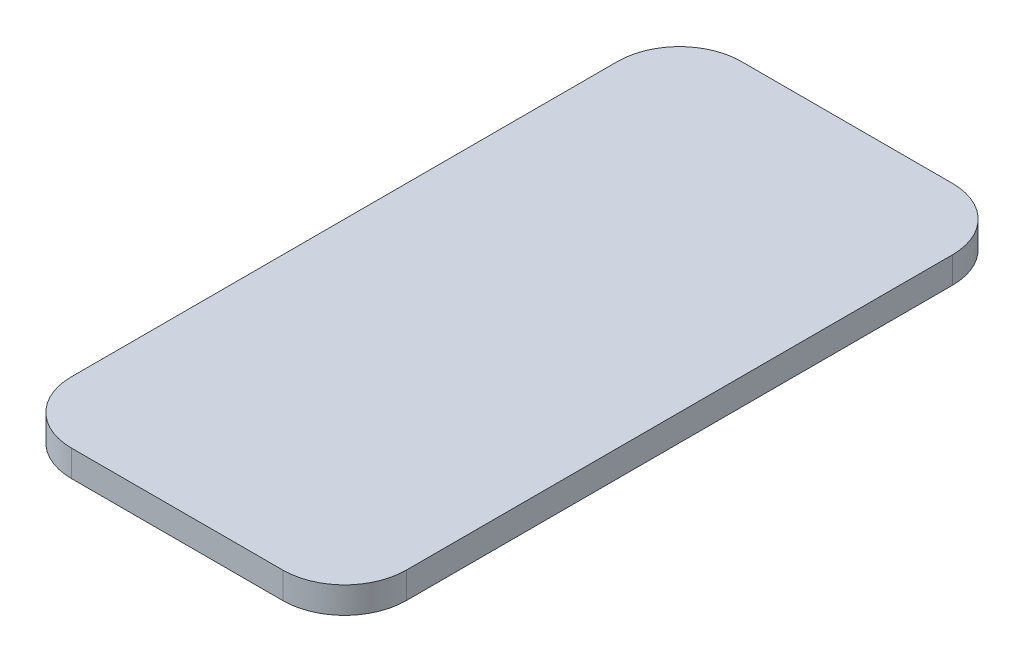
SolidWorks part; units mm, degrees
material "EN8"
ref_plane "Front Plane" through (0, 0, 0) normal (0, 0, 1) x (1, 0, 0)
ref_plane "Top Plane" through (0, 0, 0) normal (0, 1, 0) x (1, 0, 0)
ref_plane "Right Plane" through (0, 0, 0) normal (1, 0, 0) x (0, 0, -1)
sketch "Sketch1" plane through (0, 0, 0) normal (0, 1, 0) x (1, 0, 0)
  line L1 (-12, -38) -> (12, -38)
  line L2 (-19, -31) -> (-19, 31)
  line L3 (-12, 38) -> (12, 38)
  line L4 (19, -31) -> (19, 31)
  line L5 (-19, -38) -> (19, 38) construction
  line L6 (-19, 38) -> (19, -38) construction
  arc A0 (-12, -38) -> (-19, -31) centre (-12, -31) cw
  arc A1 (12, -38) -> (19, -31) centre (12, -31) ccw
  arc A2 (12, 38) -> (19, 31) centre (12, 31) cw
  arc A3 (-19, 31) -> (-12, 38) centre (-12, 31) cw
  point P0 (0, 0)
  dimension "D3" = 7
  dimension "D1" = 76
  dimension "D2" = 38
extrude "Boss-Extrude1" add sketch "Sketch1" along normal blind 3
